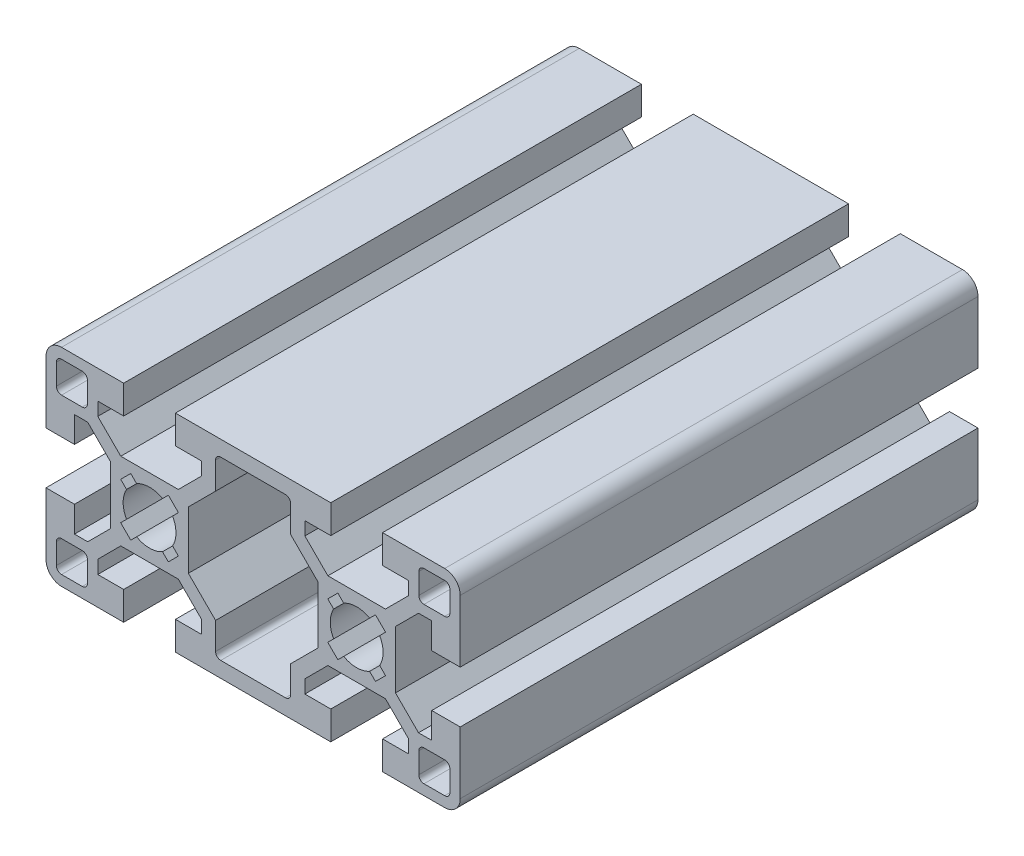
SolidWorks part; units mm, degrees
material "Aluminium"
ref_plane "Front Plane" through (0, 0, 0) normal (0, 0, 1) x (1, 0, 0)
ref_plane "Top Plane" through (0, 0, 0) normal (0, 1, 0) x (1, 0, 0)
ref_plane "Right Plane" through (0, 0, 0) normal (1, 0, 0) x (0, 0, -1)
sketch "Sketch1" plane through (0, 0, 0) normal (0, 0, 1) x (1, 0, 0)
  line L0 (-38, 13) -> (-38, 17)
  line L1 (-37, 18) -> (-33, 18)
  line L2 (-32, 17) -> (-32, 13)
  line L3 (-33, 12) -> (-37, 12)
  line L4 (-15.555, -2.5004) -> (-14.4237, -3.6318)
  line L5 (-14.4237, -3.6318) -> (-16.3682, -5.5763)
  line L6 (-16.3682, -5.5763) -> (-17.4996, -4.445)
  line L7 (-22.5004, -4.445) -> (-23.6318, -5.5763)
  line L8 (-23.6318, -5.5763) -> (-25.5763, -3.6318)
  line L9 (-25.5763, -3.6318) -> (-24.445, -2.5004)
  line L10 (-24.445, 2.5004) -> (-25.5763, 3.6318)
  line L11 (-25.5763, 3.6318) -> (-23.6318, 5.5763)
  line L12 (-23.6318, 5.5763) -> (-22.5004, 4.445)
  line L13 (-17.4996, 4.445) -> (-16.3682, 5.5763)
  line L14 (-16.3682, 5.5763) -> (-14.4237, 3.6318)
  line L15 (-14.4237, 3.6318) -> (-15.555, 2.5004)
  line L16 (-38, -17) -> (-38, -13)
  line L17 (-37, -12) -> (-33, -12)
  line L18 (-32, -13) -> (-32, -17)
  line L19 (-33, -18) -> (-37, -18)
  line L20 (38, -13) -> (38, -17)
  line L21 (37, -18) -> (33, -18)
  line L22 (32, -17) -> (32, -13)
  line L23 (33, -12) -> (37, -12)
  line L24 (15.555, 2.5004) -> (14.4237, 3.6318)
  line L25 (14.4237, 3.6318) -> (16.3682, 5.5763)
  line L26 (16.3682, 5.5763) -> (17.4996, 4.445)
  line L27 (22.5004, 4.445) -> (23.6318, 5.5763)
  line L28 (23.6318, 5.5763) -> (25.5763, 3.6318)
  line L29 (25.5763, 3.6318) -> (24.445, 2.5004)
  line L30 (24.445, -2.5004) -> (25.5763, -3.6318)
  line L31 (25.5763, -3.6318) -> (23.6318, -5.5763)
  line L32 (23.6318, -5.5763) -> (22.5004, -4.445)
  line L33 (17.4996, -4.445) -> (16.3682, -5.5763)
  line L34 (16.3682, -5.5763) -> (14.4237, -3.6318)
  line L35 (14.4237, -3.6318) -> (15.555, -2.5004)
  line L36 (38, 17) -> (38, 13)
  line L37 (37, 12) -> (33, 12)
  line L38 (32, 13) -> (32, 17)
  line L39 (33, 18) -> (37, 18)
  line L40 (6.25, -17) -> (-6.25, -17)
  line L41 (-7.25, -16) -> (-7.25, -10.8055)
  line L42 (-7.25, -10.8055) -> (-12.5, -5.5555)
  line L43 (-12.5, -5.5555) -> (-12.5, 5.5555)
  line L44 (-12.5, 5.5555) -> (-7.25, 10.8055)
  line L45 (-7.25, 10.8055) -> (-7.25, 16)
  line L46 (-6.25, 17) -> (6.25, 17)
  line L47 (7.25, 16) -> (7.25, 10.8055)
  line L48 (7.25, 10.8055) -> (12.5, 5.5555)
  line L49 (12.5, 5.5555) -> (12.5, -5.5555)
  line L50 (12.5, -5.5555) -> (7.25, -10.8055)
  line L51 (7.25, -10.8055) -> (7.25, -16)
  line L52 (-15, -20) -> (15, -20)
  line L53 (15, -20) -> (15, -14.5)
  line L54 (15, -14.5) -> (10, -14.5)
  line L55 (10, -14.5) -> (10, -11.9445)
  line L56 (10, -11.9445) -> (14.4445, -7.5)
  line L57 (14.4445, -7.5) -> (25.5555, -7.5)
  line L58 (25.5555, -7.5) -> (30, -11.9445)
  line L59 (30, -11.9445) -> (30, -14.5)
  line L60 (30, -14.5) -> (25, -14.5)
  line L61 (25, -14.5) -> (25, -20)
  line L62 (25, -20) -> (37, -20)
  line L63 (40, -17) -> (40, -5)
  line L64 (40, -5) -> (34.5, -5)
  line L65 (34.5, -5) -> (34.5, -10)
  line L66 (34.5, -10) -> (31.9445, -10)
  line L67 (31.9445, -10) -> (27.5, -5.5555)
  line L68 (27.5, -5.5555) -> (27.5, 5.5555)
  line L69 (27.5, 5.5555) -> (31.9445, 10)
  line L70 (31.9445, 10) -> (34.5, 10)
  line L71 (34.5, 10) -> (34.5, 5)
  line L72 (34.5, 5) -> (40, 5)
  line L73 (40, 5) -> (40, 17)
  line L74 (37, 20) -> (25, 20)
  line L75 (25, 20) -> (25, 14.5)
  line L76 (25, 14.5) -> (30, 14.5)
  line L77 (30, 14.5) -> (30, 11.9445)
  line L78 (30, 11.9445) -> (25.5555, 7.5)
  line L79 (25.5555, 7.5) -> (14.4445, 7.5)
  line L80 (14.4445, 7.5) -> (10, 11.9445)
  line L81 (10, 11.9445) -> (10, 14.5)
  line L82 (10, 14.5) -> (15, 14.5)
  line L83 (15, 14.5) -> (15, 20)
  line L84 (15, 20) -> (-15, 20)
  line L85 (-15, 20) -> (-15, 14.5)
  line L86 (-15, 14.5) -> (-10, 14.5)
  line L87 (-10, 14.5) -> (-10, 11.9445)
  line L88 (-10, 11.9445) -> (-14.4445, 7.5)
  line L89 (-14.4445, 7.5) -> (-25.5555, 7.5)
  line L90 (-25.5555, 7.5) -> (-30, 11.9445)
  line L91 (-30, 11.9445) -> (-30, 14.5)
  line L92 (-30, 14.5) -> (-25, 14.5)
  line L93 (-25, 14.5) -> (-25, 20)
  line L94 (-25, 20) -> (-37, 20)
  line L95 (-40, 17) -> (-40, 5)
  line L96 (-40, 5) -> (-34.5, 5)
  line L97 (-34.5, 5) -> (-34.5, 10)
  line L98 (-34.5, 10) -> (-31.9445, 10)
  line L99 (-31.9445, 10) -> (-27.5, 5.5555)
  line L100 (-27.5, 5.5555) -> (-27.5, -5.5555)
  line L101 (-27.5, -5.5555) -> (-31.9445, -10)
  line L102 (-31.9445, -10) -> (-34.5, -10)
  line L103 (-34.5, -10) -> (-34.5, -5)
  line L104 (-34.5, -5) -> (-40, -5)
  line L105 (-40, -5) -> (-40, -17)
  line L106 (-37, -20) -> (-25, -20)
  line L107 (-25, -20) -> (-25, -14.5)
  line L108 (-25, -14.5) -> (-30, -14.5)
  line L109 (-30, -14.5) -> (-30, -11.9445)
  line L110 (-30, -11.9445) -> (-25.5555, -7.5)
  line L111 (-25.5555, -7.5) -> (-14.4445, -7.5)
  line L112 (-14.4445, -7.5) -> (-10, -11.9445)
  line L113 (-10, -11.9445) -> (-10, -14.5)
  line L114 (-10, -14.5) -> (-15, -14.5)
  line L115 (-15, -14.5) -> (-15, -20)
  arc A0 (-38, 17) -> (-37, 18) centre (-37, 17) cw
  arc A1 (-33, 18) -> (-32, 17) centre (-33, 17) cw
  arc A2 (-32, 13) -> (-33, 12) centre (-33, 13) cw
  arc A3 (-37, 12) -> (-38, 13) centre (-37, 13) cw
  arc A4 (-15.555, 2.5004) -> (-15.555, -2.5004) centre (-20, 0) cw
  arc A5 (-17.4996, -4.445) -> (-22.5004, -4.445) centre (-20, 0) cw
  arc A6 (-24.445, -2.5004) -> (-24.445, 2.5004) centre (-20, 0) cw
  arc A7 (-22.5004, 4.445) -> (-17.4996, 4.445) centre (-20, 0) cw
  arc A8 (-38, -13) -> (-37, -12) centre (-37, -13) cw
  arc A9 (-33, -12) -> (-32, -13) centre (-33, -13) cw
  arc A10 (-32, -17) -> (-33, -18) centre (-33, -17) cw
  arc A11 (-37, -18) -> (-38, -17) centre (-37, -17) cw
  arc A12 (38, -17) -> (37, -18) centre (37, -17) cw
  arc A13 (33, -18) -> (32, -17) centre (33, -17) cw
  arc A14 (32, -13) -> (33, -12) centre (33, -13) cw
  arc A15 (37, -12) -> (38, -13) centre (37, -13) cw
  arc A16 (15.555, -2.5004) -> (15.555, 2.5004) centre (20, 0) cw
  arc A17 (17.4996, 4.445) -> (22.5004, 4.445) centre (20, 0) cw
  arc A18 (24.445, 2.5004) -> (24.445, -2.5004) centre (20, 0) cw
  arc A19 (22.5004, -4.445) -> (17.4996, -4.445) centre (20, 0) cw
  arc A20 (38, 13) -> (37, 12) centre (37, 13) cw
  arc A21 (33, 12) -> (32, 13) centre (33, 13) cw
  arc A22 (32, 17) -> (33, 18) centre (33, 17) cw
  arc A23 (37, 18) -> (38, 17) centre (37, 17) cw
  arc A24 (-6.25, -17) -> (-7.25, -16) centre (-6.25, -16) cw
  arc A25 (-7.25, 16) -> (-6.25, 17) centre (-6.25, 16) cw
  arc A26 (6.25, 17) -> (7.25, 16) centre (6.25, 16) cw
  arc A27 (7.25, -16) -> (6.25, -17) centre (6.25, -16) cw
  arc A28 (37, -20) -> (40, -17) centre (37, -17) ccw
  arc A29 (40, 17) -> (37, 20) centre (37, 17) ccw
  arc A30 (-37, 20) -> (-40, 17) centre (-37, 17) ccw
  arc A31 (-40, -17) -> (-37, -20) centre (-37, -17) ccw
extrude "Boss-Extrude1" add sketch "Sketch1" against normal mid plane 100
